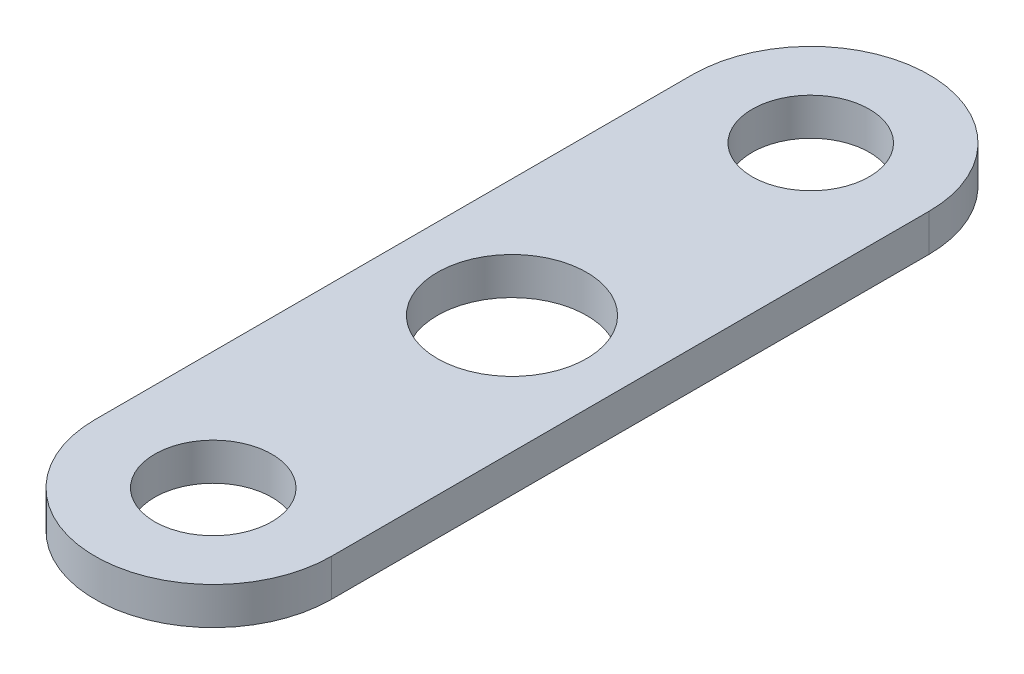
SolidWorks part; units mm, degrees
material "6061-T6 (SS)"
ref_plane "Front Plane" through (0, 0, 0) normal (0, 0, 1) x (1, 0, 0)
ref_plane "Top Plane" through (0, 0, 0) normal (0, 1, 0) x (1, 0, 0)
ref_plane "Right Plane" through (0, 0, 0) normal (1, 0, 0) x (0, 0, -1)
sketch "Sketch1" plane through (0, 0, 0) normal (0, 1, 0) x (1, 0, 0)
  line L0 (0, 12.7) -> (0, -12.7) construction
  line L1 (5.0292, -12.7) -> (5.0292, 12.7)
  line L2 (-5.0292, 12.7) -> (-5.0292, -12.7)
  circle A0 centre (0, 0) radius 3.175
  circle A1 centre (0, 12.7) radius 2.4892
  circle A2 centre (0, -12.7) radius 2.4892
  arc A3 (-5.0292, -12.7) -> (5.0292, -12.7) centre (0, -12.7) ccw
  arc A4 (5.0292, 12.7) -> (-5.0292, 12.7) centre (0, 12.7) ccw
  point P7 (0, 0)
  dimension "D1" = 6.35
  dimension "D2" = 4.9784
  dimension "D4" = 2.54
  dimension "D3" = 25.4
extrude "Boss-Extrude1" add sketch "Sketch1" along normal blind 1.5875
